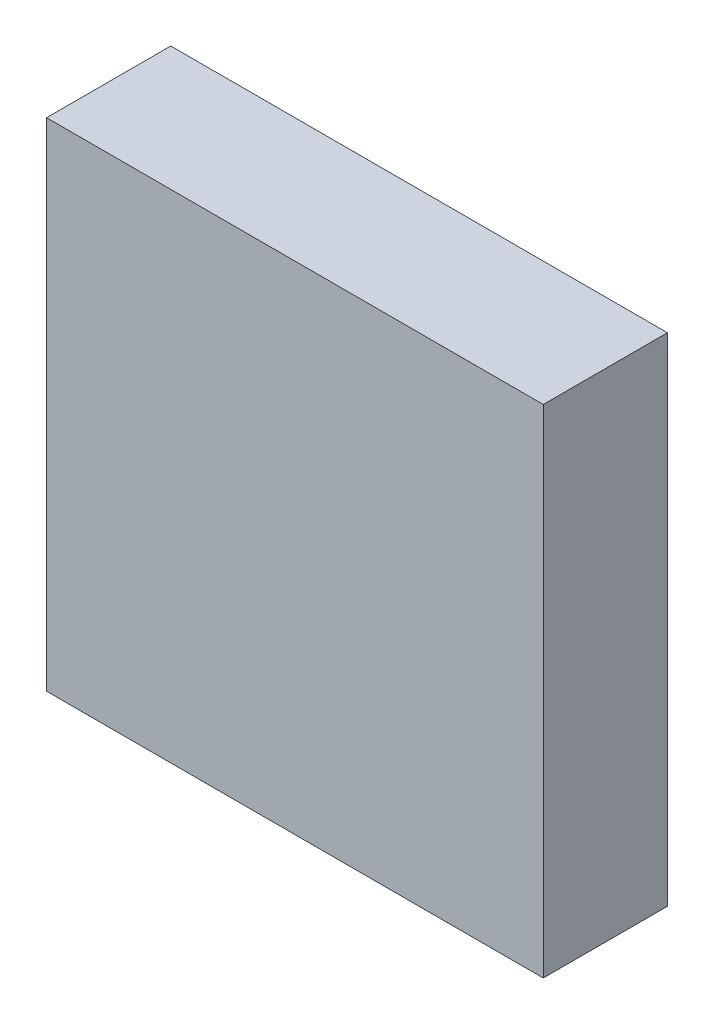
SolidWorks part; units mm, degrees
ref_plane "Front Plane" through (0, 0, 0) normal (0, 0, 1) x (1, 0, 0)
ref_plane "Top Plane" through (0, 0, 0) normal (0, 1, 0) x (1, 0, 0)
ref_plane "Right Plane" through (0, 0, 0) normal (1, 0, 0) x (0, 0, -1)
other "Configuration Table"
sketch "Sketch1" plane through (0, 0, 0) normal (0, 0, 1) x (1, 0, 0)
  line L1 (0, 0) -> (120, 0)
  line L2 (0, 0) -> (0, 120)
  line L3 (0, 120) -> (120, 120)
  line L4 (120, 0) -> (120, 120)
  dimension "D1" = 120
  dimension "D2" = 120
extrude "Boss-Extrude1" add sketch "Sketch1" along normal blind 30
